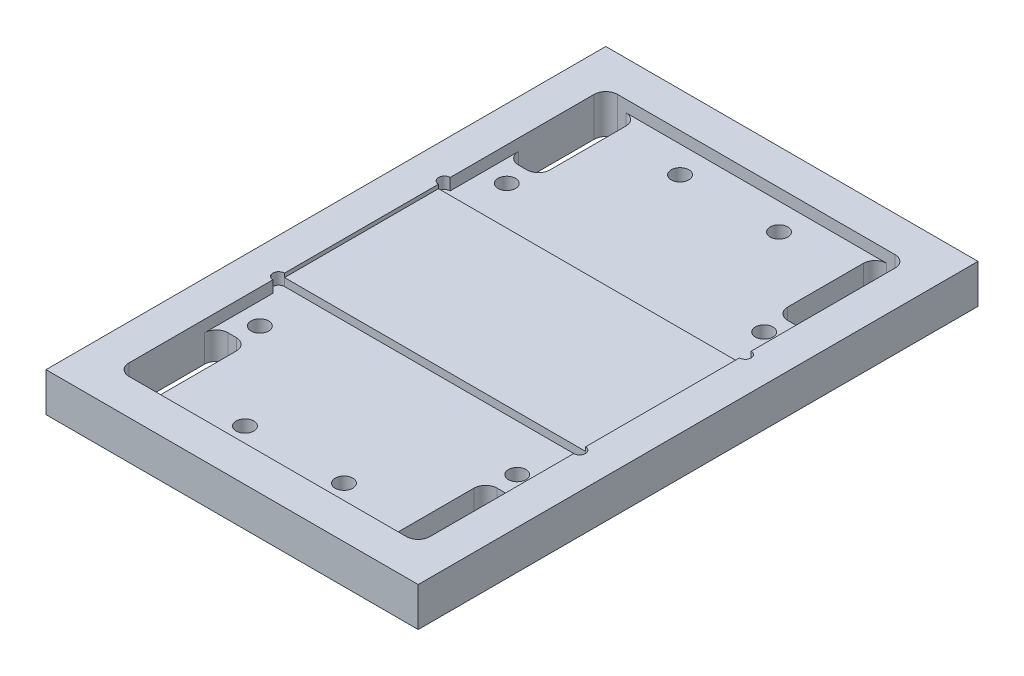
SolidWorks part; units mm, degrees
ref_plane "Front Plane" through (0, 0, 0) normal (0, 0, 1) x (1, 0, 0)
ref_plane "Top Plane" through (0, 0, 0) normal (0, 1, 0) x (1, 0, 0)
ref_plane "Right Plane" through (0, 0, 0) normal (1, 0, 0) x (0, 0, -1)
sketch "Sketch1" plane through (0, 0, 0) normal (0, 1, 0) x (1, 0, 0)
  line L1 (-23.876, -35.908) -> (23.876, -35.908)
  line L2 (-23.876, -35.908) -> (-23.876, 35.908)
  line L3 (-23.876, 35.908) -> (23.876, 35.908)
  line L4 (23.876, -35.908) -> (23.876, 35.908)
  line L5 (-23.876, -35.908) -> (23.876, 35.908) construction
  line L6 (-23.876, 35.908) -> (23.876, -35.908) construction
  line L7 (-19.05, 10.127) -> (19.05, 10.127) construction
  line L8 (-19.05, 10.127) -> (-19.05, 31.082) construction
  line L9 (-19.05, 31.082) -> (19.05, 31.082) construction
  line L10 (19.05, 10.127) -> (19.05, 31.082) construction
  line L11 (-19.05, 10.127) -> (19.05, 31.082) construction
  line L12 (-19.05, 31.082) -> (19.05, 10.127) construction
  line L13 (-5, -10) -> (5, -10) construction
  line L14 (-5, -10) -> (-5, 10) construction
  line L15 (-5, 10) -> (5, 10) construction
  line L16 (5, -10) -> (5, 10) construction
  line L17 (-5, -10) -> (5, 10) construction
  line L18 (-5, 10) -> (5, -10) construction
  point P0 (0, 0)
  point P6 (0, 20.6045)
  point P11 (0, 0)
  dimension "D1" = 20
  dimension "D2" = 10
  dimension "D3" = 0.127
  dimension "D4" = 38.1
  dimension "D5" = 20.955
  dimension "D6" = 4.826
  dimension "D7" = 4.826
extrude "Boss-Extrude1" add sketch "Sketch1" along normal blind 5
sketch "Sketch2" plane through (0, 5, 0) normal (0, 1, 0) x (1, 0, 0)
  line L0 (23.876, 35.908) -> (-23.876, 35.908) construction
  line L1 (-19.304, -31.336) -> (19.304, -31.336)
  line L2 (-19.304, -31.336) -> (-19.304, 31.336)
  line L3 (-19.304, 31.336) -> (19.304, 31.336)
  line L4 (19.304, -31.336) -> (19.304, 31.336)
  line L5 (-19.304, -31.336) -> (19.304, 31.336) construction
  line L6 (-19.304, 31.336) -> (19.304, -31.336) construction
  line L7 (-23.876, 35.908) -> (-23.876, -35.908) construction
  point P0 (0, 0)
  dimension "D1" = 4.572
  dimension "D2" = 4.572
extrude "Cut-Extrude1" cut sketch "Sketch2" against normal blind 1.5
sketch "Sketch3" plane through (0, 3.5, 0) normal (0, 1, 0) x (1, 0, 0)
  line L1 (-19.304, 31.336) -> (-15.24, 31.336)
  line L2 (-19.304, 31.336) -> (-19.304, 18.636)
  line L3 (-19.304, 18.636) -> (-15.24, 18.636)
  line L4 (-15.24, 31.336) -> (-15.24, 18.636)
  dimension "D1" = 12.7
  dimension "D2" = 4.064
extrude "Cut-Extrude2" cut sketch "Sketch3" against normal through all
mirror "Mirror4" about plane through (0, 0, 0) normal (0, 0, 1) of "Cut-Extrude2" second plane through (0, 0, 0) second plane normal (1, 0, 0)
fillet "Fillet2" radius 1.5 16 edges at (19.304, 2.5, -31.336) (19.304, 2.5, 31.336) (-19.304, 2.5, 31.336) (-19.304, 2.5, -31.336) (-19.304, 1.75, -18.636) (-15.24, 1.75, -31.336) (-15.24, 1.75, -18.636) (19.304, 1.75, -18.636) (15.24, 1.75, -18.636) (15.24, 1.75, -31.336) (-19.304, 1.75, 18.636) (-15.24, 1.75, 18.636) (-15.24, 1.75, 31.336) (19.304, 1.75, 18.636) (15.24, 1.75, 31.336) (15.24, 1.75, 18.636)
sketch "Sketch4" plane through (0, 3.5, 0) normal (0, 1, 0) x (1, 0, 0)
  line L0 (0, 0) -> (0, 31.336) construction
  line L1 (17.804, 31.336) -> (-17.804, 31.336) construction
  line L2 (-19.304, 31.082) -> (19.304, 31.082) construction
  line L3 (-19.304, 29.836) -> (-19.304, -29.836) construction
  line L4 (19.304, -29.836) -> (19.304, 29.836) construction
  circle A0 centre (-6.35, 27.907) radius 1.1303
  circle A1 centre (-16.51, 15.842) radius 1.1303
  dimension "D3" = 3.175
  dimension "D4" = 2.2606
  dimension "D5" = 33.02
  dimension "D6" = 15.24
  dimension "D7" = 2.2606
  dimension "D1" = 0.254
  dimension "D2" = 12.7
extrude "Cut-Extrude3" cut sketch "Sketch4" against normal through all
mirror "Mirror5" about plane through (0, 0, 0) normal (0, 0, 1) of "Cut-Extrude3" second plane through (0, 0, 0) second plane normal (1, 0, 0)
sketch "Sketch5" plane through (0, 3.5, 0) normal (0, 1, 0) x (1, 0, 0)
  line L0 (19.304, -29.836) -> (19.304, 29.836) construction
  line L1 (-19.304, -9.875) -> (19.304, -9.875)
  line L2 (-19.304, -9.875) -> (-19.304, 9.875)
  line L3 (-19.304, 9.875) -> (19.304, 9.875)
  line L4 (19.304, -9.875) -> (19.304, 9.875)
  line L5 (-19.304, -9.875) -> (19.304, 9.875) construction
  line L6 (-19.304, 9.875) -> (19.304, -9.875) construction
  point P0 (0, 0)
  dimension "D1" = 19.75
extrude "Boss-Extrude2" add sketch "Sketch5" along normal blind 1
sketch "Sketch6" plane through (0, 5, 0) normal (0, 1, 0) x (1, 0, 0)
  line L0 (-19.304, 29.836) -> (-19.304, -29.836) construction
  line L1 (-19.304, 11.375) -> (-19.304, 9.875)
  arc A0 (-19.304, 9.875) -> (-19.304, 11.375) centre (-19.304, 10.625) cw
  dimension "D1" = 0.75
extrude "Cut-Extrude4" cut sketch "Sketch6" against normal up to surface (1.5 mm away) up to face at (-16.51, 3.5, -14.7117)
mirror "Mirror6" about plane through (0, 0, 0) normal (0, 0, 1) of "Cut-Extrude4" second plane through (0, 0, 0) second plane normal (1, 0, 0)
